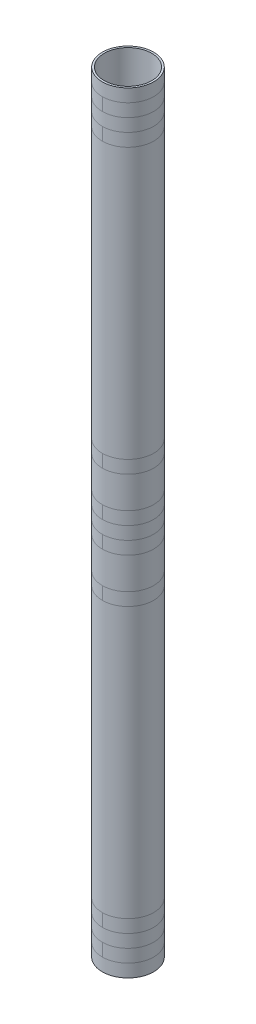
SolidWorks part; units mm, degrees
material "6063-O"
ref_plane "Front Plane" through (0, 0, 0) normal (0, 0, 1) x (1, 0, 0)
ref_plane "Top Plane" through (0, 0, 0) normal (0, 1, 0) x (1, 0, 0)
ref_plane "Right Plane" through (0, 0, 0) normal (1, 0, 0) x (0, 0, -1)
sketch "Sketch1" plane through (0, 0, 0) normal (0, 1, 0) x (1, 0, 0)
  circle A0 centre (0, 0) radius 20
  dimension "D1" = 40
extrude "Boss-Extrude1" add sketch "Sketch1" along normal blind 600
sketch "Sketch5" plane through (0, 600, 0) normal (0, 1, 0) x (1, 0, 0)
  circle A0 centre (0, 0) radius 18.5
  dimension "D1" = 37
extrude "Cut-Extrude1" cut sketch "Sketch5" against normal blind 600
ref_plane "Plane1" through (30, 0, 0) normal (1, 0, 0) x (0, 0, -1)
sketch "Sketch6" plane through (30, 0, 0) normal (1, 0, 0) x (0, 0, -1)
  line L0 (-20, 0) -> (20, 0) construction
  line L1 (-20, 600) -> (-20, 0) construction
  circle A0 centre (-5, 279.5) radius 2.5
  circle A1 centre (-5, 325.5) radius 2.5
  circle A2 centre (20, 300) radius 2.5
  dimension "D1" = 279.5
  dimension "D3" = 15
  dimension "D4" = 40
  dimension "D5" = 46
  dimension "D6" = 300
  dimension "D2" = 15
sketch "Sketch10" plane through (30, 0, 0) normal (1, 0, 0) x (0, 0, -1)
  line L0 (-20, 10) -> (20, 10)
  line L1 (-20, 600) -> (-20, 0) construction
  line L2 (20, 0) -> (20, 600) construction
  line L3 (20, 10) -> (20, 20)
  line L4 (20, 20) -> (-20, 20)
  line L5 (-20, 20) -> (-20, 10)
  line L6 (-20, 590) -> (20, 590)
  line L7 (20, 590) -> (20, 580)
  line L8 (20, 580) -> (-20, 580)
  line L9 (-20, 580) -> (-20, 590)
  line L10 (-20, 570) -> (20, 570)
  line L11 (20, 570) -> (20, 560)
  line L12 (20, 560) -> (-20, 560)
  line L13 (-20, 560) -> (-20, 570)
  line L14 (-20, 30) -> (-20, 40)
  line L15 (-20, 40) -> (20, 40)
  line L16 (20, 40) -> (20, 30)
  line L17 (20, 30) -> (-20, 30)
  line L18 (-20, 0) -> (20, 0) construction
  line L19 (20, 600) -> (-20, 600) construction
  line L20 (-20, 295) -> (20, 295)
  line L21 (20, 295) -> (20, 285)
  line L22 (20, 285) -> (-20, 285)
  line L23 (-20, 285) -> (-20, 295)
  line L24 (-20, 315) -> (20, 315)
  line L25 (20, 315) -> (20, 305)
  line L26 (20, 305) -> (-20, 305)
  line L27 (-20, 305) -> (-20, 315)
  dimension "D1" = 10
  dimension "D2" = 10
  dimension "D3" = 10
  dimension "D4" = 10
  dimension "D5" = 10
  dimension "D6" = 10
  dimension "D7" = 10
  dimension "D8" = 10
  dimension "D9" = 10
  dimension "D10" = 10
  dimension "D11" = 10
split line "Split Line2"
sketch "Sketch11" plane through (30, 0, 0) normal (1, 0, 0) x (0, 0, -1)
  line L0 (-20, 349.58) -> (-20, 339.58)
  line L1 (-20, 560) -> (-20, 315) construction
  line L2 (-20, 260.42) -> (-20, 250.42)
  line L3 (-20, 285) -> (-20, 40) construction
  line L4 (-20, 285) -> (20, 285) construction
  line L5 (20, 315) -> (-20, 315) construction
  line L6 (-20, 349.58) -> (0, 349.58)
  line L8 (0, 339.58) -> (-20, 339.58)
  line L9 (-20, 260.42) -> (0, 260.42)
  line L11 (0, 250.42) -> (-20, 250.42)
  line L12 (0, 349.58) -> (20, 349.58)
  line L13 (20, 315) -> (20, 560) construction
  line L14 (20, 349.58) -> (20, 339.58)
  line L15 (20, 339.58) -> (0, 339.58)
  line L16 (0, 260.42) -> (20, 260.42)
  line L17 (20, 40) -> (20, 285) construction
  line L18 (20, 260.42) -> (20, 250.42)
  line L19 (20, 250.42) -> (0, 250.42)
  dimension "D1" = 24.58
  dimension "D2" = 10
  dimension "D3" = 24.58
  dimension "D4" = 10
split line "Split Line6"
ref_plane "Plane2" through (0, 0, 30) normal (0, 0, 1) x (1, 0, 0)
sketch "Sketch9" plane through (0, 0, 30) normal (0, 0, 1) x (1, 0, 0)
  line L0 (-17.7777, 586.4464) -> (17.9432, 586.4464)
  line L1 (17.9432, 586.4464) -> (17.9432, 538.4114)
  line L2 (17.9432, 538.4114) -> (-17.7777, 538.4114)
  line L3 (-17.7777, 538.4114) -> (-17.7777, 586.4464)
  line L4 (-17.7777, 10.5086) -> (17.9432, 10.5086)
  line L5 (17.9432, 10.5086) -> (17.9432, 58.7449)
  line L6 (17.9432, 58.7449) -> (-17.7777, 58.7449)
  line L7 (-17.7777, 58.7449) -> (-17.7777, 10.5086)
  circle A0 centre (-7.8259, 575.72) radius 2.5
  circle A1 centre (7.9699, 575.72) radius 2.5
  circle A2 centre (-7.8259, 559.1861) radius 2.5
  circle A3 centre (7.9699, 559.1861) radius 2.5
  circle A4 centre (-7.8259, 45.6469) radius 2.5
  circle A5 centre (7.9699, 45.6469) radius 2.5
  circle A6 centre (7.9699, 28.7529) radius 2.5
  circle A7 centre (-7.8259, 28.7529) radius 2.5
